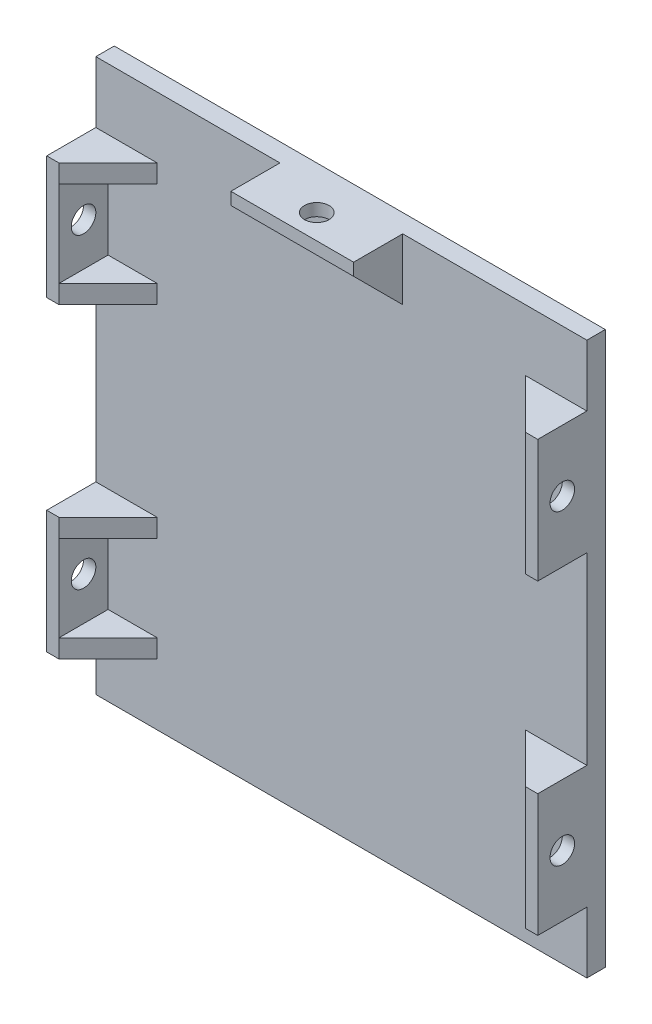
SolidWorks part; units mm, degrees
ref_plane "Front Plane" through (0, 0, 0) normal (0, 0, 1) x (1, 0, 0)
ref_plane "Top Plane" through (0, 0, 0) normal (0, 1, 0) x (1, 0, 0)
ref_plane "Right Plane" through (0, 0, 0) normal (1, 0, 0) x (0, 0, -1)
sketch "Sketch1" plane through (0, 0, 0) normal (0, 0, 1) x (1, 0, 0)
  line L1 (0, 0) -> (80, 0)
  line L2 (0, 0) -> (0, 90)
  line L3 (0, 90) -> (80, 90)
  line L4 (80, 0) -> (80, 90)
  dimension "D1" = 90
  dimension "D2" = 80
extrude "Boss-Extrude1" add sketch "Sketch1" along normal blind 3
sketch "Sketch2" plane through (0, 0, 3) normal (0, 0, 1) x (1, 0, 0)
  line L0 (0, 90) -> (0, 0) construction
  line L1 (0, 80) -> (10, 80)
  line L2 (0, 80) -> (0, 60)
  line L3 (0, 60) -> (10, 60)
  line L4 (10, 80) -> (10, 77)
  line L5 (80, 90) -> (0, 90) construction
  line L6 (10, 77) -> (2, 77)
  line L7 (2, 77) -> (2, 63)
  line L8 (2, 63) -> (10, 63)
  line L9 (10, 63) -> (10, 60)
  dimension "D1" = 10
  dimension "D2" = 20
  dimension "D3" = 3
  dimension "D4" = 3
  dimension "D5" = 2
  dimension "D6" = 10
extrude "Boss-Extrude2" add sketch "Sketch2" along normal blind 8
sketch "Sketch3" plane through (0, 80, 0) normal (0, 1, 0) x (1, 0, 0)
  line L0 (10, -3) -> (2, -11)
  line L1 (10, -11) -> (0, -11) construction
  line L2 (2, -11) -> (10, -11)
  line L3 (10, -11) -> (10, -3)
  line L4 (10, -3) -> (0, -3) construction
  dimension "D1" = 45
extrude "Cut-Extrude1" cut sketch "Sketch3" against normal through all
sketch "Sketch6" plane through (2, 0, 0) normal (1, 0, 0) x (0, 0, -1)
  line L0 (-11, 63) -> (-11, 77) construction
  line L1 (-11, 80) -> (-3, 80) construction
  circle A0 centre (-7, 70) radius 2
  dimension "D1" = 4
  dimension "D2" = 10
extrude "Cut-Extrude3" cut sketch "Sketch6" against normal blind 25
ref_plane "Plane1" through (40, 0, 0) normal (1, 0, 0) x (0, 0, -1)
ref_plane "Plane3" through (0, 45, 0) normal (0, -1, 0) x (-1, 0, 0)
mirror "Mirror4" about plane through (40, 0, 0) normal (1, 0, 0) of "Cut-Extrude3", "Boss-Extrude2", "Cut-Extrude1"
mirror "Mirror5" about plane through (0, 45, 0) normal (0, -1, 0) of "Boss-Extrude2", "Cut-Extrude1", "Mirror4", "Cut-Extrude3"
sketch "Sketch4" plane through (0, 0, 3) normal (0, 0, 1) x (1, 0, 0)
  line L0 (80, 90) -> (0, 90) construction
  line L1 (30, 90) -> (50, 90)
  line L2 (30, 90) -> (30, 80)
  line L3 (30, 80) -> (33, 80)
  line L4 (50, 90) -> (50, 80)
  line L5 (40, -1.65) -> (40, 1.65) construction
  line L6 (33, 80) -> (33, 88)
  line L7 (33, 88) -> (47, 88)
  line L8 (47, 88) -> (47, 80)
  line L9 (47, 80) -> (50, 80)
  dimension "D1" = 20
  dimension "D2" = 10
  dimension "D3" = 10
  dimension "D4" = 3
  dimension "D5" = 3
  dimension "D6" = 2
extrude "Boss-Extrude3" add sketch "Sketch4" along normal blind 8
sketch "Sketch5" plane through (30, 0, 0) normal (-1, 0, 0) x (0, 0, 1)
  line L0 (3, 80) -> (11, 88)
  line L1 (11, 90) -> (11, 80) construction
  line L2 (11, 88) -> (11, 80)
  line L3 (11, 80) -> (3, 80)
  line L4 (3, 90) -> (3, 80) construction
  dimension "D1" = 45
extrude "Cut-Extrude2" cut sketch "Sketch5" against normal blind 25
sketch "Sketch7" plane through (0, 88, 0) normal (0, -1, 0) x (1, 0, 0)
  line L0 (33, 11) -> (47, 11) construction
  line L1 (50, 11) -> (50, 3) construction
  circle A0 centre (40, 7) radius 2
  dimension "D1" = 4
  dimension "D2" = 4
  dimension "D3" = 10
extrude "Cut-Extrude4" cut sketch "Sketch7" against normal blind 25
equation "\"D4@Sketch2\"=\"D3@Sketch2\""
